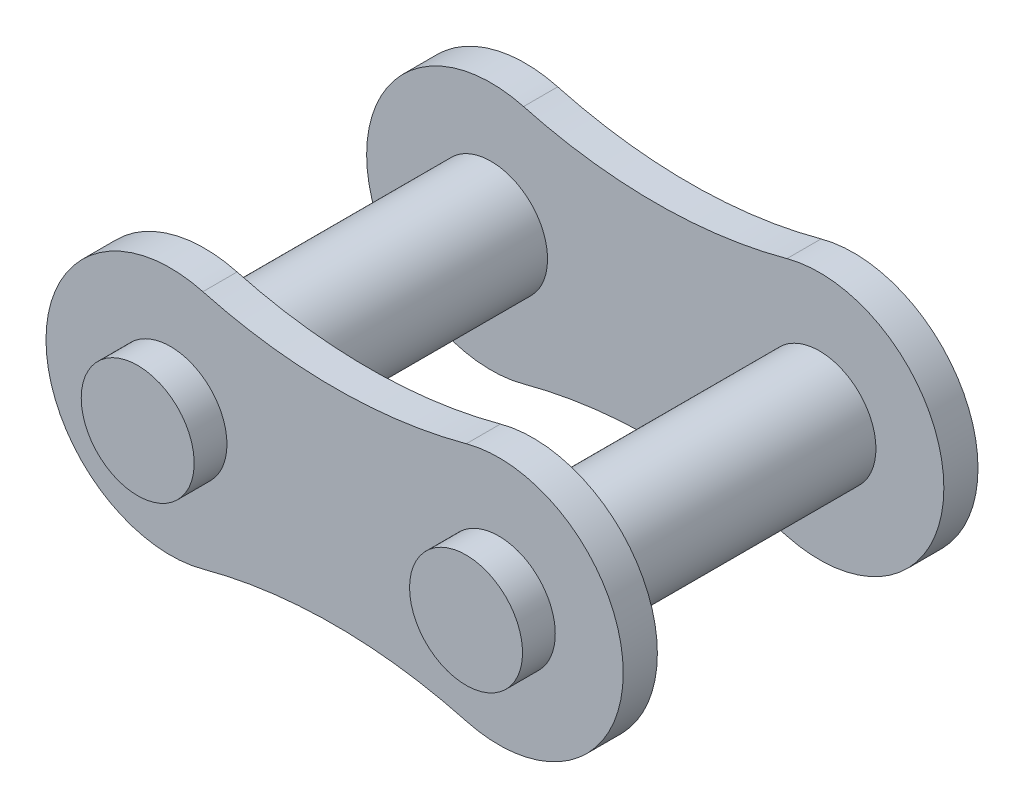
SolidWorks part; units mm, degrees
material "1023 Carbon Steel Sheet (SS)"
ref_plane "Front Plane" through (0, 0, 0) normal (0, 0, 1) x (1, 0, 0)
ref_plane "Top Plane" through (0, 0, 0) normal (0, 1, 0) x (1, 0, 0)
ref_plane "Right Plane" through (0, 0, 0) normal (1, 0, 0) x (0, 0, -1)
sketch "Sketch1" plane through (0, 0, 0) normal (0, 0, 1) x (1, 0, 0)
  line L0 (-4.7625, 0) -> (4.7625, 0) construction
  line L1 (-4.7625, 4.1021) -> (-4.7625, -4.1021) construction
  line L2 (0, -3.4868) -> (0, 3.4868) construction
  circle A0 centre (-4.7625, 0) radius 3.175
  circle A1 centre (4.7625, 0) radius 3.175
  circle A2 centre (-4.7625, 0) radius 1.6383
  circle A3 centre (4.7625, 0) radius 1.6383
  arc A4 (-3.7199, 3.9674) -> (-3.7199, -3.9674) centre (-4.7625, 0) ccw
  arc A5 (3.7199, -3.9674) -> (3.7199, 3.9674) centre (4.7625, 0) ccw
  arc A6 (-3.7199, 3.9674) -> (3.7199, 3.9674) centre (0, 18.1231) ccw
  arc A7 (-3.7199, -3.9674) -> (3.7199, -3.9674) centre (0, -18.1231) cw
  dimension "Roller Dia" = 6.35
  dimension "Pin Dia" = 3.2766
  dimension "Pitch" = 9.525
  dimension "H" = 8.2042
  dimension "D2" = 6.9736
sketch "Sketch2" plane through (0, 0, 0) normal (0, 1, 0) x (1, 0, 0)
  line L0 (0, 2.86) -> (0, -2.86) construction
  point P2 (0, -4.1046)
  point P4 (0, 4.1046)
  point P5 (0, 4.1554)
  point P6 (0, 5.146)
  dimension "W" = 5.72
  dimension "T" = 1.2446
  dimension "D1" = 1.2446
  dimension "T1" = 0.9906
  dimension "D3" = 0.0508
ref_plane "Plane1" through (0, 0, 2.86) normal (0, 0, 1) x (1, 0, 0)
ref_plane "Plane2" through (0, 0, -4.1554) normal (0, 0, 1) x (1, 0, 0)
sketch "Sketch7" plane through (0, 0, -4.1554) normal (0, 0, 1) x (1, 0, 0)
  line L0 (14.2875, 3.6098) -> (14.2875, -3.6098) construction
  arc A0 (5.7047, 3.4847) -> (5.7047, -3.4847) centre (4.7625, 0) ccw
  arc A1 (13.3453, -3.4847) -> (13.3453, 3.4847) centre (14.2875, 0) ccw
  arc A2 (3.7199, -3.9674) -> (3.7199, 3.9674) centre (4.7625, 0) ccw construction
  arc A4 (5.7047, 3.4847) -> (13.3453, 3.4847) centre (9.525, 17.6136) ccw
  arc A5 (5.7047, -3.4847) -> (13.3453, -3.4847) centre (9.525, -17.6136) cw
  arc A6 (-3.7199, 3.9674) -> (3.7199, 3.9674) centre (0, 18.1231) ccw construction
  circle A8 centre (4.7625, 0) radius 1.6383
  circle A9 centre (14.2875, 0) radius 1.6383
  dimension "D2" = 7.2197
extrude "Boss-Extrude3" add sketch "Sketch7" against normal up to vertex (0.9906 mm away) separate body up to point (0, 0, -5.146)
mirror "Mirror1" about plane through (0, 0, 0) normal (0, 0, 1) of bodies 105 103
sketch "Sketch8" plane through (0, 0, 0) normal (0, 0, 1) x (1, 0, 0)
  circle A0 centre (4.7625, 0) radius 1.6383
  circle A1 centre (14.2875, 0) radius 1.6383
  circle A2 centre (4.7625, 0) radius 1.6383 construction
  circle A3 centre (14.2875, 0) radius 1.6383 construction
extrude "Boss-Extrude4" add sketch "Sketch8" against normal blind 6.096 and the other way blind 6.096 separate body
equation "\"D2@Sketch1\" =\"H@Sketch1\"*.85"
equation "\"D1@Sketch2\" = \"T@Sketch2\""
equation "\"D2@Sketch7\" = \"H@Sketch1\"*.88"
